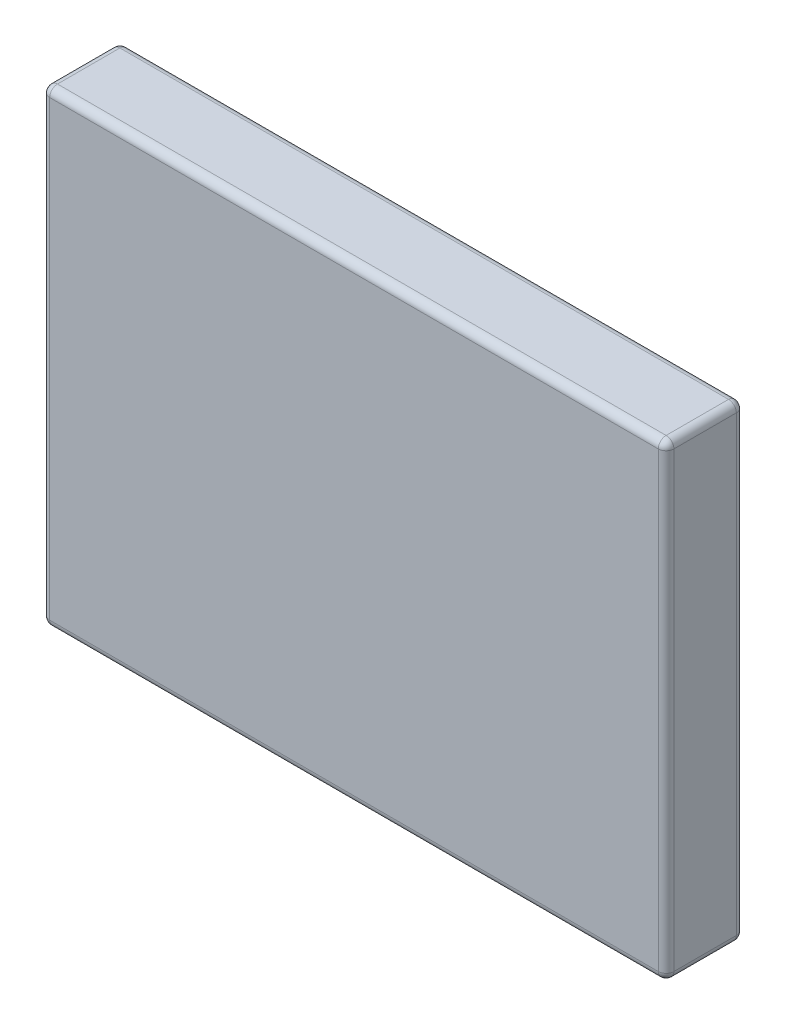
SolidWorks part; units mm, degrees
ref_plane "Front Plane" through (0, 0, 0) normal (0, 0, 1) x (1, 0, 0)
ref_plane "Top Plane" through (0, 0, 0) normal (0, 1, 0) x (1, 0, 0)
ref_plane "Right Plane" through (0, 0, 0) normal (1, 0, 0) x (0, 0, -1)
sketch "Sketch1" plane through (0, 0, 0) normal (0, 0, 1) x (1, 0, 0)
  line L1 (0, 0) -> (101.6, 0)
  line L2 (0, 0) -> (0, 76.2)
  line L3 (0, 76.2) -> (101.6, 76.2)
  line L4 (101.6, 0) -> (101.6, 76.2)
extrude "Boss-Extrude1" add sketch "Sketch1" along normal blind 12.7
fillet "Fillet2" radius 1.27 12 edges at (0, 38.1, 0) (50.8, 0, 0) (101.6, 38.1, 0) (50.8, 76.2, 0) (0, 38.1, 12.7) (50.8, 0, 12.7) (101.6, 38.1, 12.7) (50.8, 76.2, 12.7) (0, 76.2, 6.35) (101.6, 76.2, 6.35) (101.6, 0, 6.35) (0, 0, 6.35)
